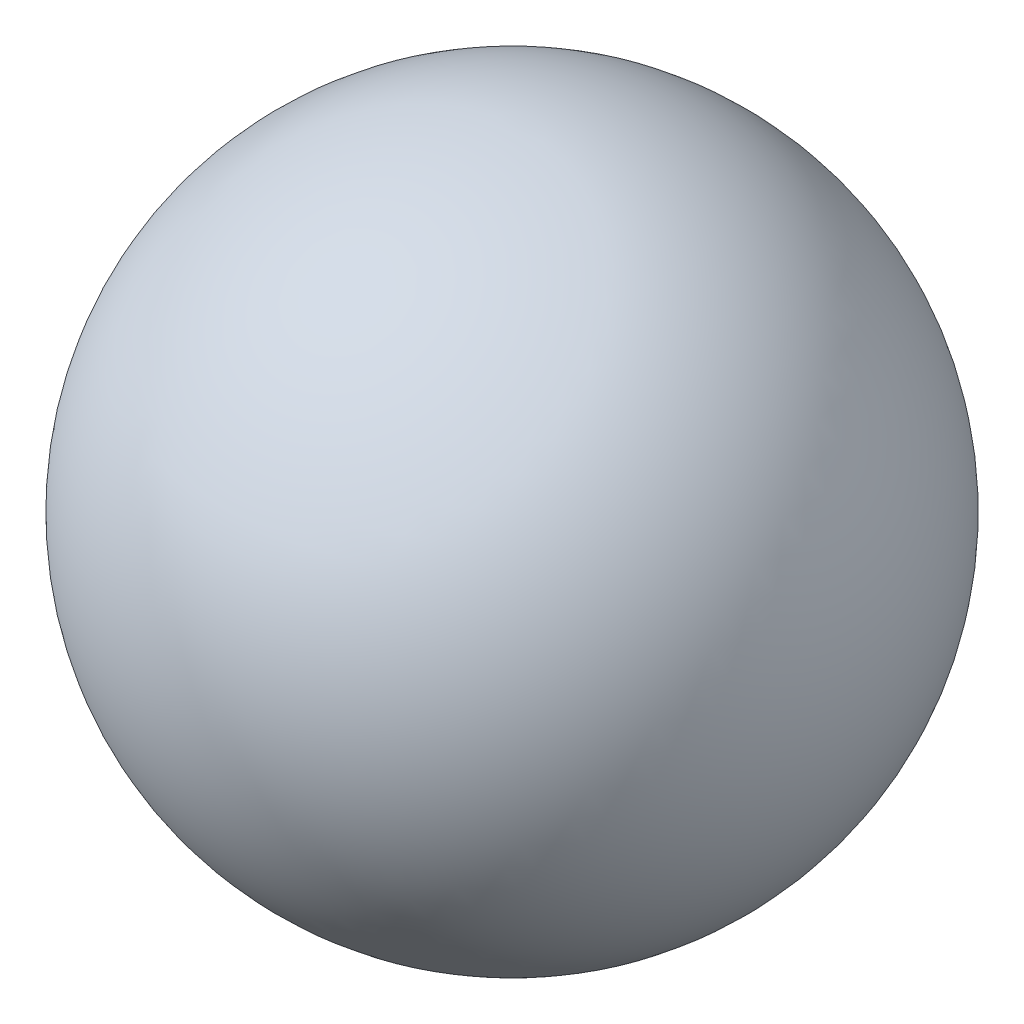
SolidWorks part; units mm, degrees
ref_plane "Front Plane" through (0, 0, 0) normal (0, 0, 1) x (1, 0, 0)
ref_plane "Top Plane" through (0, 0, 0) normal (0, 1, 0) x (1, 0, 0)
ref_plane "Right Plane" through (0, 0, 0) normal (1, 0, 0) x (0, 0, -1)
sketch "Sketch1" plane through (0, 0, 0) normal (0, 0, 1) x (1, 0, 0)
  line L0 (0, 21) -> (0, -21)
  arc A0 (0, 21) -> (0, -21) centre (0, 0) cw
  point P4 (14.9856, 21)
  dimension "D1" = 42
revolve "Revolve1" add sketch "Sketch1" angle 360 about L0
